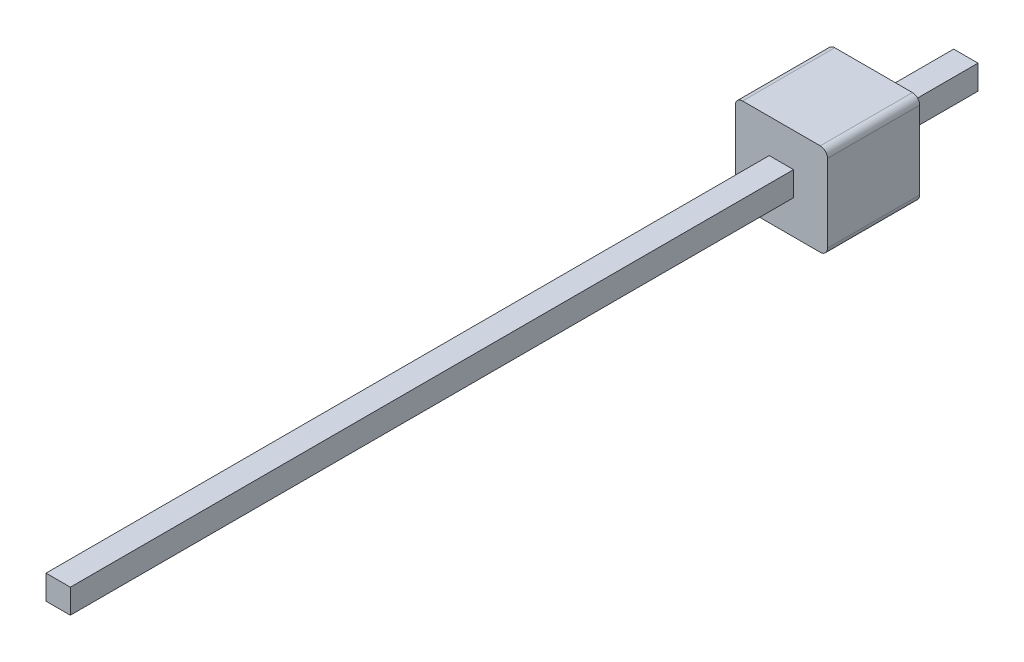
SolidWorks part; units mm, degrees
ref_plane "前视基准面" through (0, 0, 0) normal (0, 0, 1) x (1, 0, 0)
ref_plane "上视基准面" through (0, 0, 0) normal (0, 1, 0) x (1, 0, 0)
ref_plane "右视基准面" through (0, 0, 0) normal (1, 0, 0) x (0, 0, -1)
sketch "草图1" plane through (0, 0, 0) normal (0, 0, 1) x (1, 0, 0)
  line L0 (0, 5.3599) -> (0, -8.0108) construction
  line L1 (-1.27, 1.27) -> (1.27, 1.27)
  line L2 (-1.27, 1.27) -> (-1.27, -1.27)
  line L3 (-1.27, -1.27) -> (1.27, -1.27)
  line L4 (1.27, 1.27) -> (1.27, -1.27)
  line L5 (-4.9446, 0) -> (3.8946, 0) construction
  dimension "D1" = 2.54
  dimension "D2" = 2.54
extrude "拉伸1" add sketch "草图1" along normal blind 2.54
sketch "草图2" plane through (0, 0, 0) normal (0, 0, -1) x (-1, 0, 0)
  line L1 (0.335, -0.335) -> (-0.335, -0.335)
  line L2 (0.335, -0.335) -> (0.335, 0.335)
  line L3 (0.335, 0.335) -> (-0.335, 0.335)
  line L4 (-0.335, -0.335) -> (-0.335, 0.335)
  line L5 (0.335, -0.335) -> (-0.335, 0.335) construction
  line L6 (0.335, 0.335) -> (-0.335, -0.335) construction
  point P0 (0, 0)
  dimension "D1" = 0.67
  dimension "D2" = 0.67
extrude "凸台-拉伸1" add sketch "草图2" along normal blind 2.54
sketch "草图3" plane through (0, 0, 2.54) normal (0, 0, 1) x (1, 0, 0)
  line L1 (0.335, -0.335) -> (-0.335, -0.335)
  line L2 (0.335, -0.335) -> (0.335, 0.335)
  line L3 (0.335, 0.335) -> (-0.335, 0.335)
  line L4 (-0.335, -0.335) -> (-0.335, 0.335)
  line L5 (0.335, -0.335) -> (-0.335, 0.335) construction
  line L6 (0.335, 0.335) -> (-0.335, -0.335) construction
  point P0 (0, 0)
  dimension "D1" = 0.67
  dimension "D2" = 0.67
extrude "凸台-拉伸2" add sketch "草图3" along normal offset from surface (19.92 mm away) 25 up to face at (0, 0, -2.54)
fillet "圆角1" radius 0.2 4 edges at (-1.27, 1.27, 1.27) (-1.27, -1.27, 1.27) (1.27, -1.27, 1.27) (1.27, 1.27, 1.27)
